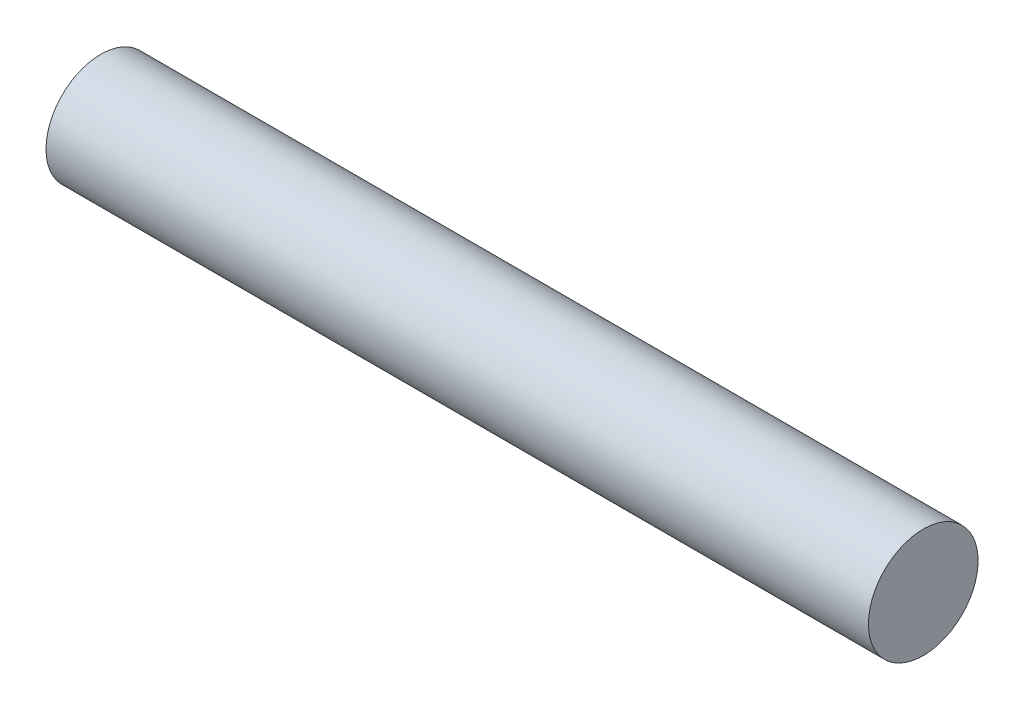
SolidWorks part; units mm, degrees
ref_plane "前视基准面" through (0, 0, 0) normal (0, 0, 1) x (1, 0, 0)
ref_plane "上视基准面" through (0, 0, 0) normal (0, 1, 0) x (1, 0, 0)
ref_plane "右视基准面" through (0, 0, 0) normal (1, 0, 0) x (0, 0, -1)
other "Configuration Table"
sketch "旋转轮廓" plane through (0, 0, 0) normal (0, 0, 1) x (1, 0, 0)
  line L0 (-0.5, 0) -> (120.5, 0) construction
  line L1 (120, 0) -> (120, 8)
  line L2 (120, 8) -> (0, 8)
  line L3 (0, 8) -> (0, 0)
  line L4 (0, 0) -> (120, 0)
revolve "旋转" add sketch "旋转轮廓" angle 360 about L0
